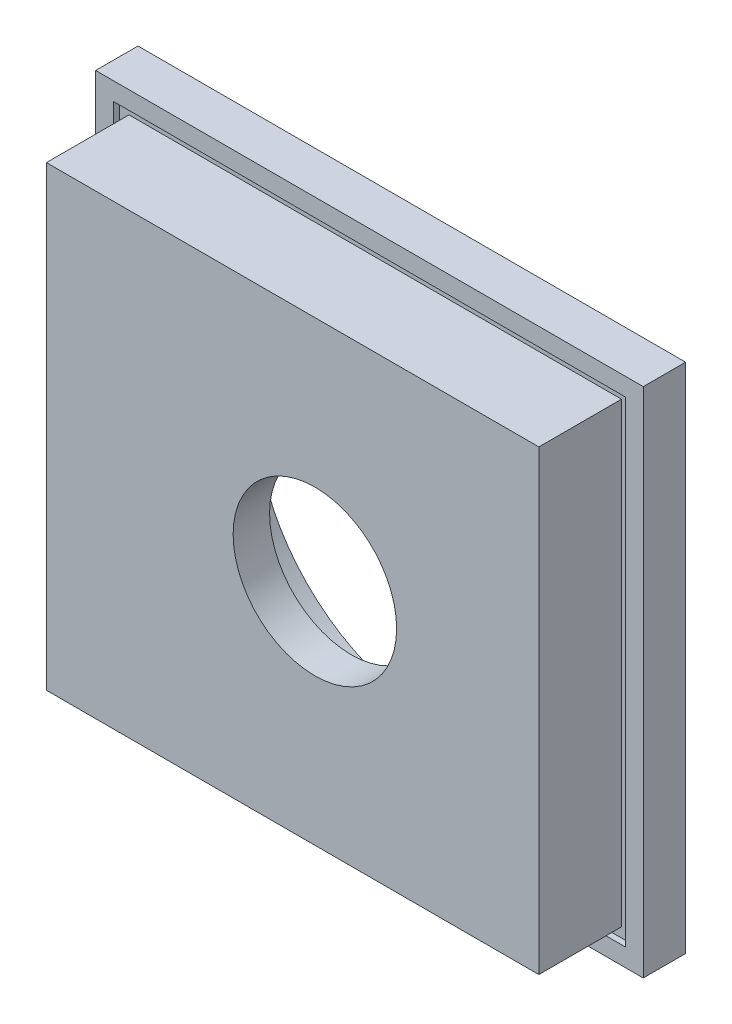
SolidWorks part; units mm, degrees
ref_plane "Front Plane" through (0, 0, 0) normal (0, 0, 1) x (1, 0, 0)
ref_plane "Top Plane" through (0, 0, 0) normal (0, 1, 0) x (1, 0, 0)
ref_plane "Right Plane" through (0, 0, 0) normal (1, 0, 0) x (0, 0, -1)
sketch "Sketch1" plane through (0, 0, 0) normal (0, 0, 1) x (1, 0, 0)
  line L1 (0, 0) -> (278, 0)
  line L2 (0, 0) -> (0, 260)
  line L3 (0, 260) -> (278, 260)
  line L4 (278, 0) -> (278, 260)
  dimension "D1" = 278
  dimension "D2" = 260
extrude "Boss-Extrude1" add sketch "Sketch1" along normal blind 60.5
sketch "Sketch2" plane through (0, 0, 0) normal (0, 0, 1) x (1, 0, 0)
  line L0 (0, 260) -> (0, 0) construction
  line L5 (278, 260) -> (0, 260) construction
  circle A0 centre (150.3, 130) radius 90.5
  point P5 (0, 130)
  point P9 (139, 260)
  dimension "D1" = 181
  dimension "D2" = 11.3
extrude "Cut-Extrude2" cut sketch "Sketch2" along normal blind 42
sketch "Sketch3" plane through (0, 0, 0) normal (0, 0, 1) x (1, 0, 0)
  circle A0 centre (150.3, 130) radius 41.5
  circle A1 centre (150.3, 130) radius 90.5 construction
  dimension "D1" = 83
extrude "Cut-Extrude3" cut sketch "Sketch3" along normal through all
sketch "Sketch4" plane through (0, 0, 0) normal (0, 0, 1) x (1, 0, 0)
  circle A0 centre (150.3, 130) radius 99.95
  circle A1 centre (150.3, 130) radius 95.05
  dimension "D1" = 190.1
  dimension "D2" = 199.9
extrude "Cut-Extrude5" cut sketch "Sketch4" along normal blind 2.95
sketch "Sketch5" plane through (0, 0, 0) normal (0, 0, 1) x (1, 0, 0)
  line L0 (150.3, 22.5) -> (150.3, 237.5) construction
  line L1 (150.3, 130) -> (204.05, 223.0977) construction
  line L2 (150.3, 130) -> (96.55, 223.0977) construction
  line L3 (150.3, 130) -> (96.55, 36.9023) construction
  line L4 (150.3, 130) -> (204.05, 36.9023) construction
  circle A0 centre (150.3, 130) radius 107.5 construction
  point P4 (96.55, 223.0977)
  point P5 (42.8, 130)
  point P6 (204.05, 36.9023)
  point P7 (96.55, 36.9023)
  point P8 (257.8, 130)
  point P14 (204.05, 223.0977)
  dimension "D1" = 215
  dimension "D2" = 30
  dimension "D3" = 30
  dimension "D4" = 30
  dimension "D5" = 30
ref_plane "Plane1" through (0, 0, 60.5) normal (0, 0, 1) x (1, 0, 0)
sketch "Sketch6" plane through (0, 0, 60.5) normal (0, 0, 1) x (1, 0, 0)
  line L1 (0, 260) -> (278, 260)
  line L2 (0, 260) -> (0, 0)
  line L3 (0, 0) -> (278, 0)
  line L4 (278, 260) -> (278, 0)
  line L5 (14, 246) -> (264, 246)
  line L6 (14, 246) -> (14, 14)
  line L7 (14, 14) -> (264, 14)
  line L8 (264, 246) -> (264, 14)
  point P10 (139, 246)
  point P11 (139, 260)
  point P12 (264, 130)
  point P13 (278, 130)
  dimension "D1" = 14
  dimension "D2" = 14
extrude "Cut-Extrude6" cut sketch "Sketch6" against normal blind 39
sketch "Sketch7" plane through (0, 0, 60.5) normal (0, 0, 1) x (1, 0, 0)
  line L1 (14, 14) -> (264, 14)
  line L2 (14, 14) -> (14, 246)
  line L3 (14, 246) -> (264, 246)
  line L4 (264, 14) -> (264, 246)
  line L5 (9.1, 250.9) -> (268.9, 250.9)
  line L6 (9.1, 250.9) -> (9.1, 9.1)
  line L7 (9.1, 9.1) -> (268.9, 9.1)
  line L8 (268.9, 250.9) -> (268.9, 9.1)
  dimension "D1" = 4.9
  dimension "D2" = 4.9
  dimension "D3" = 4.9
  dimension "D4" = 4.9
extrude "Cut-Extrude7" cut sketch "Sketch7" against normal blind 41.95
hole_wizard "Ø8.0mm Dowel Hole1" positions "Sketch8" profile "Sketch9" hole size "Ø8.0" standard "ISO"
sketch "Sketch8" plane through (0, 0, 0) normal (0, 0, -1) x (-1, 0, 0)
  point P0 (-204.05, 223.0977)
  point P3 (-96.55, 223.0977)
  point P6 (-42.8, 130)
  point P9 (-96.55, 36.9023)
  point P12 (-204.05, 36.9023)
  point P15 (-257.8, 130)
sketch "Sketch9" plane through (204.05, 223.0977, 0) normal (1, 0, 0) x (0, 1, 0)
  line L0 (0, 0) -> (0, 17.4034)
  line L1 (0, 17.4034) -> (4, 15)
  line L2 (4, 15) -> (4, 0)
  line L5 (4, 0) -> (0, 0)
  line L10 (0, 17.4034) -> (-4, 15) construction
  line L11 (0, -6.35) -> (0, 107.95) construction
  dimension "Hole Dia." = 8
  dimension "Hole Depth" = 15
  dimension "Drill Angle" = 118
sketch "Sketch10" plane through (0, 0, 0) normal (0, 1, 0) x (1, 0, 0)
  line L0 (0, 0) -> (278, 0) construction
  circle A0 centre (150.3, -9) radius 3
  point P4 (0, 0)
  dimension "D1" = 6
  dimension "D2" = 9
extrude "Cut-Extrude8" cut sketch "Sketch10" along normal blind 46
